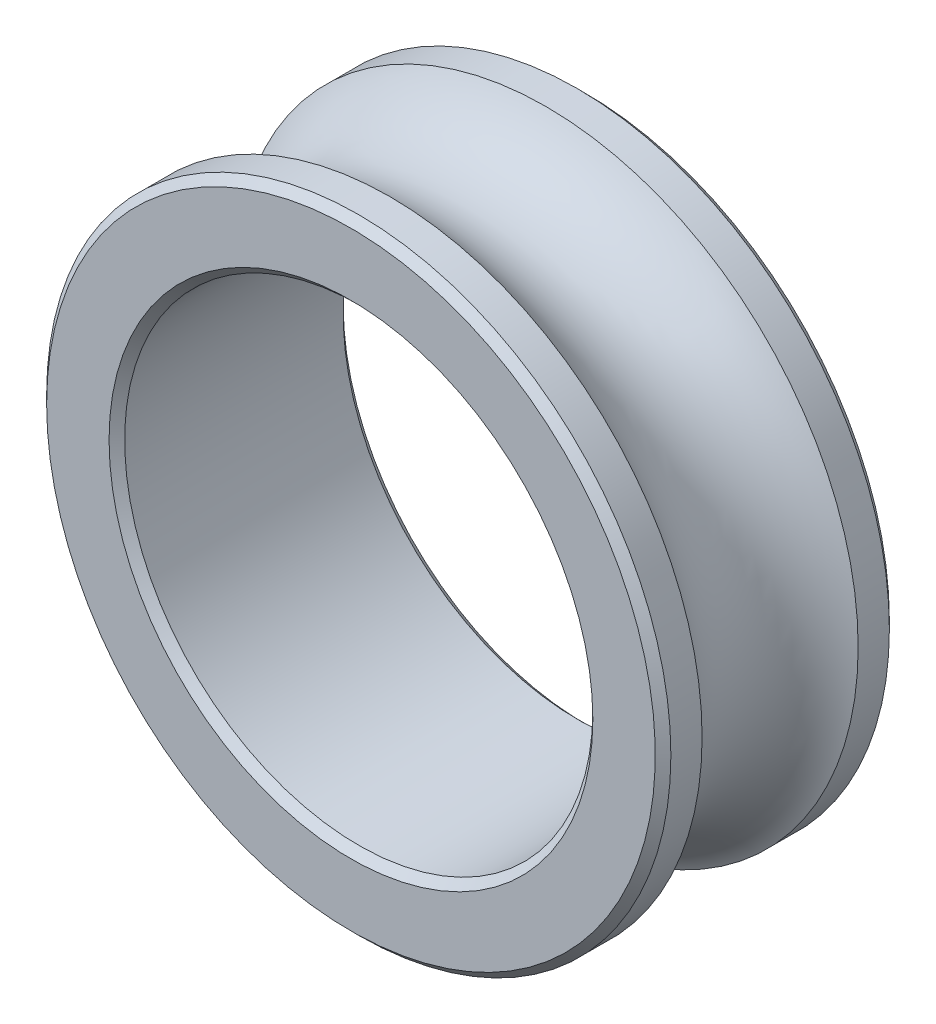
SolidWorks part; units mm, degrees
ref_plane "Front Plane" through (0, 0, 0) normal (0, 0, 1) x (1, 0, 0)
ref_plane "Top Plane" through (0, 0, 0) normal (0, 1, 0) x (1, 0, 0)
ref_plane "Right Plane" through (0, 0, 0) normal (1, 0, 0) x (0, 0, -1)
sketch "Sketch1" plane through (0, 0, 0) normal (1, 0, 0) x (0, 0, -1)
  line L0 (0, 0) -> (381, 0) construction
  line L1 (-381, 762) -> (381, 762)
  line L2 (381, 762) -> (381, 1016)
  line L3 (381, 1016) -> (254, 1016)
  line L4 (-381, 1016) -> (-254, 1016)
  line L5 (-381, 762) -> (-381, 1016)
  line L6 (0, 762) -> (0, 867.156) construction
  arc A0 (-254, 1016) -> (254, 1016) centre (0, 1156.9328) ccw
  point P6 (0, 762)
revolve "Revolve1" add sketch "Sketch1" angle 360 about L0
chamfer "Chamfer1" distance 25.4 angle 45 4 edges at (1016, 0, 381) (762, 0, 381) (1016, 0, -381) (762, 0, -381)
